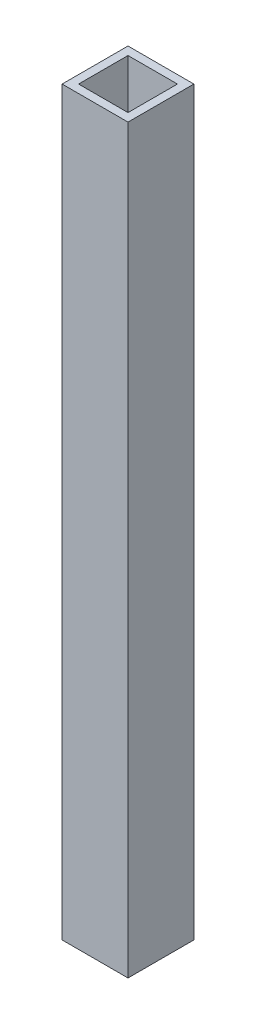
SolidWorks part; units mm, degrees
ref_plane "Piano frontale" through (0, 0, 0) normal (0, 0, 1) x (1, 0, 0)
ref_plane "Piano superiore" through (0, 0, 0) normal (0, 1, 0) x (1, 0, 0)
ref_plane "Piano destro" through (0, 0, 0) normal (1, 0, 0) x (0, 0, -1)
sketch "Schizzo1" plane through (0, 0, 0) normal (0, 1, 0) x (1, 0, 0)
  line L0 (15, 15) -> (-15, 15)
  line L1 (20, -20) -> (-20, -20)
  line L2 (20, -20) -> (20, 20)
  line L3 (20, 20) -> (-20, 20)
  line L4 (-20, -20) -> (-20, 20)
  line L5 (20, -20) -> (-20, 20) construction
  line L6 (20, 20) -> (-20, -20) construction
  line L7 (-15, -15) -> (-15, 15)
  line L8 (15, -15) -> (-15, -15)
  line L9 (15, -15) -> (15, 15)
  point P0 (0, 0)
  dimension "D1" = 40
  dimension "D2" = 40
  dimension "D3" = 5
extrude "Estrusione-Estrusione1" add sketch "Schizzo1" along normal blind 450
